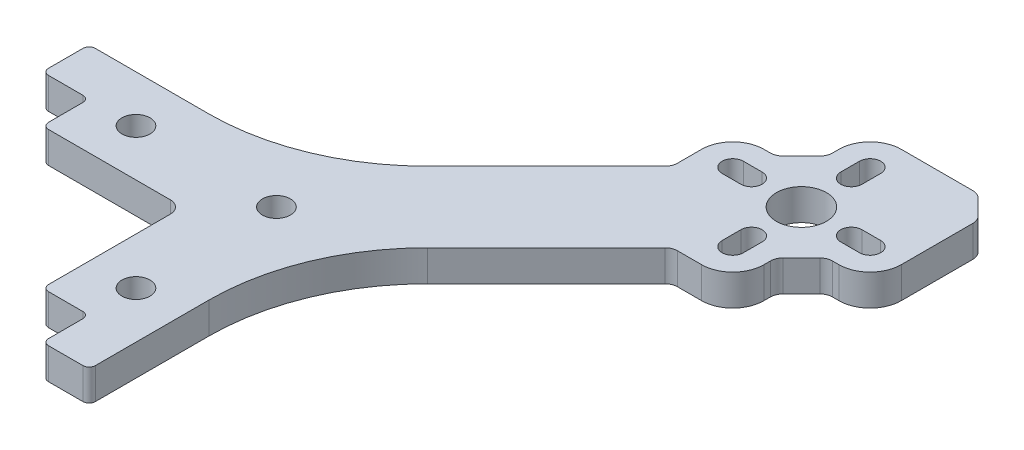
SolidWorks part; units mm, degrees
ref_plane "Front Plane" through (0, 0, 0) normal (0, 0, 1) x (1, 0, 0)
ref_plane "Top Plane" through (0, 0, 0) normal (0, 1, 0) x (1, 0, 0)
ref_plane "Right Plane" through (0, 0, 0) normal (1, 0, 0) x (0, 0, -1)
sketch "Sketch1" plane through (0, 0, 0) normal (0, 1, 0) x (1, 0, 0)
  line L0 (0, 0) -> (79.5495, 79.5495) construction
  line L1 (-45, -45) -> (45, -45) construction
  line L2 (-45, -45) -> (-45, 45) construction
  line L3 (-45, 45) -> (45, 45) construction
  line L4 (45, -45) -> (45, 45) construction
  line L5 (-45, -45) -> (45, 45) construction
  line L6 (-45, 45) -> (45, -45) construction
  line L7 (71.5495, 79.5495) -> (87.5495, 79.5495) construction
  line L8 (87.5495, 79.5495) -> (90.5495, 79.5495) construction
  line L9 (87.5495, 81.2495) -> (90.5495, 81.2495)
  line L10 (87.5495, 77.8495) -> (90.5495, 77.8495)
  line L11 (79.5495, 71.5495) -> (79.5495, 68.5495) construction
  line L12 (81.2495, 71.5495) -> (81.2495, 68.5495)
  line L13 (77.8495, 71.5495) -> (77.8495, 68.5495)
  line L14 (71.5495, 79.5495) -> (68.5495, 79.5495) construction
  line L15 (71.5495, 77.8495) -> (68.5495, 77.8495)
  line L16 (71.5495, 81.2495) -> (68.5495, 81.2495)
  line L17 (79.5495, 87.5495) -> (79.5495, 90.5495) construction
  line L18 (77.8495, 87.5495) -> (77.8495, 90.5495)
  line L19 (81.2495, 87.5495) -> (81.2495, 90.5495)
  line L20 (79.5495, 79.5495) -> (93.6916, 93.6916) construction
  line L21 (95.5495, 91.8338) -> (91.8338, 95.5495)
  line L25 (72.5796, 86.5194) -> (79.5495, 79.5495) construction
  line L28 (0, 45) -> (0, 37.5)
  line L29 (0, 37.5) -> (7.5, 37.5)
  line L30 (7.5, 37.5) -> (7.5, 30)
  line L31 (7.5, 30) -> (30, 30)
  line L32 (0, 45) -> (19.1888, 45)
  line L38 (45, 0) -> (45, 19.1888)
  line L39 (45, 0) -> (37.5, 0)
  line L40 (37.5, 0) -> (37.5, 7.5)
  line L41 (37.5, 7.5) -> (30, 7.5)
  line L42 (30, 7.5) -> (30, 30)
  line L43 (68.5495, 84.5495) -> (70.4074, 84.5495)
  line L44 (-42.5, -28) -> (42.5, -28) construction
  line L45 (-42.5, -28) -> (-42.5, 28) construction
  line L46 (-42.5, 28) -> (42.5, 28) construction
  line L47 (42.5, -28) -> (42.5, 28) construction
  line L48 (-42.5, -28) -> (42.5, 28) construction
  line L49 (-42.5, 28) -> (42.5, -28) construction
  line L50 (-19, 24.5) -> (39, 24.5) construction
  line L51 (-19, 24.5) -> (-19, -24.5) construction
  line L52 (-19, -24.5) -> (39, -24.5) construction
  line L53 (39, 24.5) -> (39, -24.5) construction
  line L54 (-19, 24.5) -> (39, -24.5) construction
  line L55 (-19, -24.5) -> (39, 24.5) construction
  line L56 (70.4074, 84.5495) -> (74.5495, 88.6916)
  line L57 (74.5495, 88.6916) -> (74.5495, 90.5495)
  line L58 (79.5495, 95.5495) -> (91.8338, 95.5495)
  line L59 (63.5495, 79.5495) -> (63.5495, 74.8632)
  line L60 (63.5495, 74.8632) -> (43.9376, 55.2513)
  line L61 (95.5495, 79.5495) -> (95.5495, 91.8338)
  line L62 (88.6916, 74.5495) -> (90.5495, 74.5495)
  line L63 (84.5495, 70.4074) -> (88.6916, 74.5495)
  line L64 (84.5495, 68.5495) -> (84.5495, 70.4074)
  line L65 (79.5495, 63.5495) -> (74.8632, 63.5495)
  line L66 (74.8632, 63.5495) -> (55.2513, 43.9376)
  circle A0 centre (79.5495, 79.5495) radius 4
  arc A1 (87.5495, 81.2495) -> (87.5495, 77.8495) centre (87.5495, 79.5495) ccw
  arc A2 (90.5495, 77.8495) -> (90.5495, 81.2495) centre (90.5495, 79.5495) ccw
  arc A3 (81.2495, 71.5495) -> (77.8495, 71.5495) centre (79.5495, 71.5495) ccw
  arc A4 (77.8495, 68.5495) -> (81.2495, 68.5495) centre (79.5495, 68.5495) ccw
  arc A5 (71.5495, 77.8495) -> (71.5495, 81.2495) centre (71.5495, 79.5495) ccw
  arc A6 (68.5495, 81.2495) -> (68.5495, 77.8495) centre (68.5495, 79.5495) ccw
  arc A7 (77.8495, 87.5495) -> (81.2495, 87.5495) centre (79.5495, 87.5495) ccw
  arc A8 (81.2495, 90.5495) -> (77.8495, 90.5495) centre (79.5495, 90.5495) ccw
  arc A11 (19.1888, 45) -> (43.9376, 55.2513) centre (19.1888, 80) ccw
  arc A14 (45, 19.1888) -> (55.2513, 43.9376) centre (80, 19.1888) cw
  arc A15 (63.5495, 79.5495) -> (68.5495, 84.5495) centre (68.5495, 79.5495) cw
  arc A16 (74.5495, 90.5495) -> (79.5495, 95.5495) centre (79.5495, 90.5495) cw
  arc A17 (90.5495, 74.5495) -> (95.5495, 79.5495) centre (90.5495, 79.5495) ccw
  arc A18 (79.5495, 63.5495) -> (84.5495, 68.5495) centre (79.5495, 68.5495) ccw
  point P0 (0, 0)
  point P8 (89.0495, 79.5495)
  point P12 (79.5495, 79.5495)
  point P18 (10, 0)
  point P20 (0, 0)
  point P21 (79.5495, 70.0495)
  point P28 (70.0495, 79.5495)
  point P35 (79.5495, 89.0495)
  point P42 (79.5495, 79.5495)
  point P87 (60.0286, 48.7149)
  point P88 (72.5796, 86.5194)
  point P89 (0, 0)
  dimension "D3" = 8
  dimension "D5" = 1.7
  dimension "D9" = 8
  dimension "D14" = 35
  dimension "D10" = 5
  dimension "D1" = 112.5
  dimension "D2" = 90
  dimension "D4" = 16
  dimension "D6" = 3
  dimension "D8" = 20
  dimension "D11" = 15
  dimension "D12" = 7.5
  dimension "D13" = 7.5
  dimension "D15" = 85
  dimension "D16" = 56
  dimension "D17" = 3.5
  dimension "D18" = 49
  dimension "D19" = 58
  dimension "D20" = 10
  dimension "D7" = 4
extrude "Boss-Extrude1" add sketch "Sketch1" along normal mid plane 5
fillet "Fillet1" radius 2 9 edges at (95.5495, 0, -91.8338) (30, 0, -30) (91.8338, 0, -95.5495) (74.8632, 0, -63.5495) (84.5495, 0, -70.4074) (88.6916, 0, -74.5495) (74.5495, 0, -88.6916) (70.4074, 0, -84.5495) (63.5495, 0, -74.8632)
fillet "Fillet2" radius 1 8 edges at (45, 0, 0) (37.5, 0, 0) (37.5, 0, -7.5) (30, 0, -7.5) (0, 0, -45) (0, 0, -37.5) (7.5, 0, -30) (7.5, 0, -37.5)
hole_wizard "M4 Clearance Hole1" positions "Sketch4" profile "Sketch3" hole size "M4" standard "ANSI Metric"
sketch "Sketch4" plane through (0, 2.5, 0) normal (0, 1, 0) x (1, 0, 0)
  line L0 (0, 0) -> (79.5495, 79.5495) construction
  line L1 (-45, 45) -> (45, 45) construction
  line L2 (45, 0) -> (45, 19.1888) construction
  line L3 (37.5, 7.5) -> (30, 7.5) construction
  line L4 (7.5, 37.5) -> (7.5, 30) construction
  point P0 (15, 37.5)
  point P2 (37.5, 15)
  point P5 (37.5, 37.5)
  point P12 (0, 0)
  point P15 (42.5, 16.8603)
  dimension "D1" = 7.5
  dimension "D2" = 7.5
  dimension "D3" = 7.5
  dimension "D4" = 7.5
sketch "Sketch3" plane through (15, 2.5, -37.5) normal (1, 0, 0) x (0, 0, 1)
  line L0 (0, 0) -> (0, 6.5519)
  line L1 (0, 6.5519) -> (2.25, 5.2)
  line L2 (2.25, 5.2) -> (2.25, 0)
  line L5 (2.25, 0) -> (0, 0)
  line L10 (0, 6.5519) -> (-2.25, 5.2) construction
  line L11 (0, -6.35) -> (0, 107.95) construction
  dimension "Hole Dia." = 4.5
  dimension "Hole Depth" = 5.2
  dimension "Drill Angle" = 118
